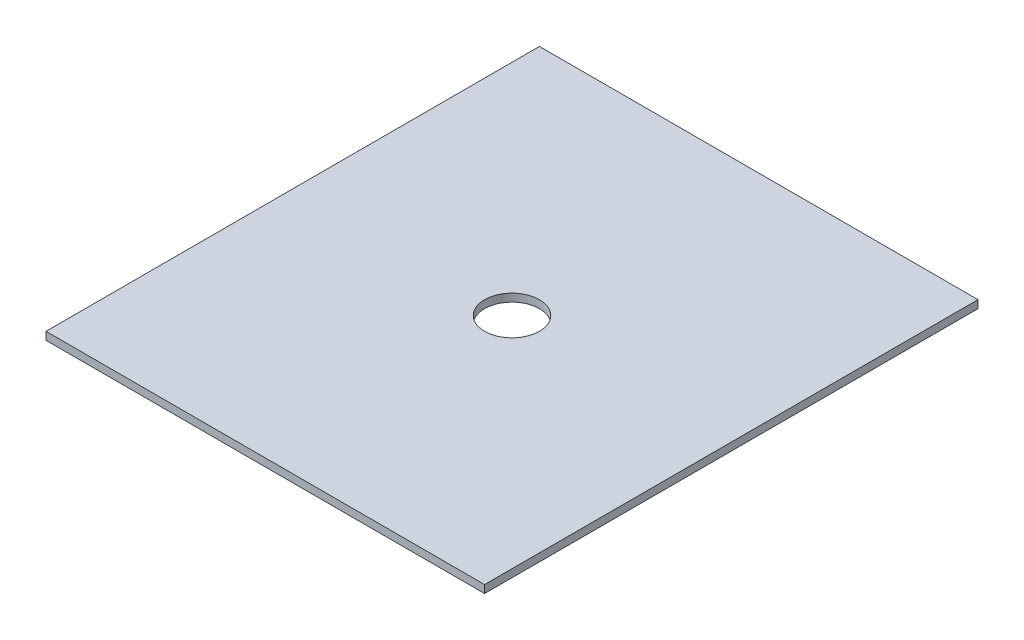
SolidWorks part; units mm, degrees
material "Maple"
ref_plane "Front Plane" through (0, 0, 0) normal (0, 0, 1) x (1, 0, 0)
ref_plane "Top Plane" through (0, 0, 0) normal (0, 1, 0) x (1, 0, 0)
ref_plane "Right Plane" through (0, 0, 0) normal (1, 0, 0) x (0, 0, -1)
sketch "Sketch1" plane through (0, 0, 0) normal (0, 1, 0) x (1, 0, 0)
  line L0 (355.6, 200.025) -> (0, 200.025) construction
  line L1 (0, 0) -> (355.6, 0)
  line L2 (0, 0) -> (0, 400.05)
  line L3 (0, 400.05) -> (355.6, 400.05)
  line L4 (355.6, 0) -> (355.6, 400.05)
  circle A0 centre (177.8, 200.025) radius 22.225
  dimension "D3" = 44.45
  dimension "D1" = 400.05
  dimension "D2" = 355.6
extrude "Boss-Extrude1" add sketch "Sketch1" along normal blind 6.35
